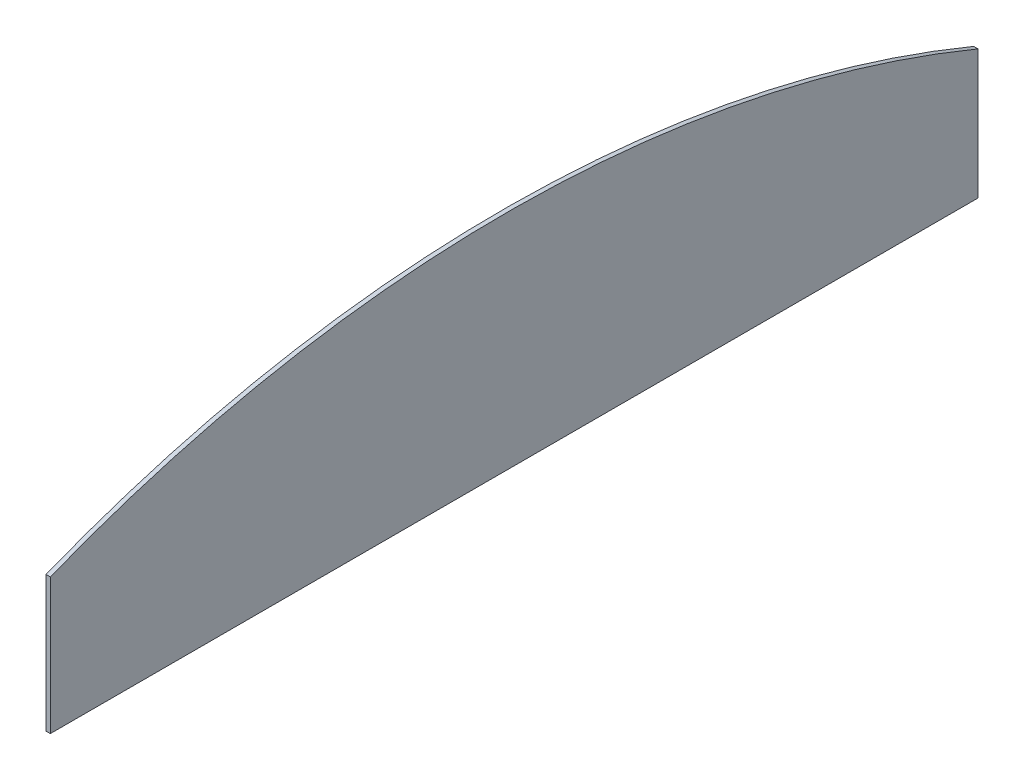
SolidWorks part; units mm, degrees
material "Galvanized Steel"
ref_plane "Front Plane" through (0, 0, 0) normal (0, 0, 1) x (1, 0, 0)
ref_plane "Top Plane" through (0, 0, 0) normal (0, 1, 0) x (1, 0, 0)
ref_plane "Right Plane" through (0, 0, 0) normal (1, 0, 0) x (0, 0, -1)
sketch "Sketch1" plane through (0, 0, 0) normal (1, 0, 0) x (0, 0, -1)
  line L1 (162.7746, 348.0321) -> (-157.2254, 348.0321)
  line L2 (-157.2254, 348.0321) -> (-157.2254, 394.8483)
  line L3 (162.7746, 348.0321) -> (162.7746, 392.5932)
  arc A0 (162.7746, 392.5932) -> (-157.2254, 394.8483) centre (0, 0) ccw
  dimension "D1" = 850
  dimension "D3" = 320
extrude "Boss-Extrude1" add sketch "Sketch1" along normal blind 1.5
